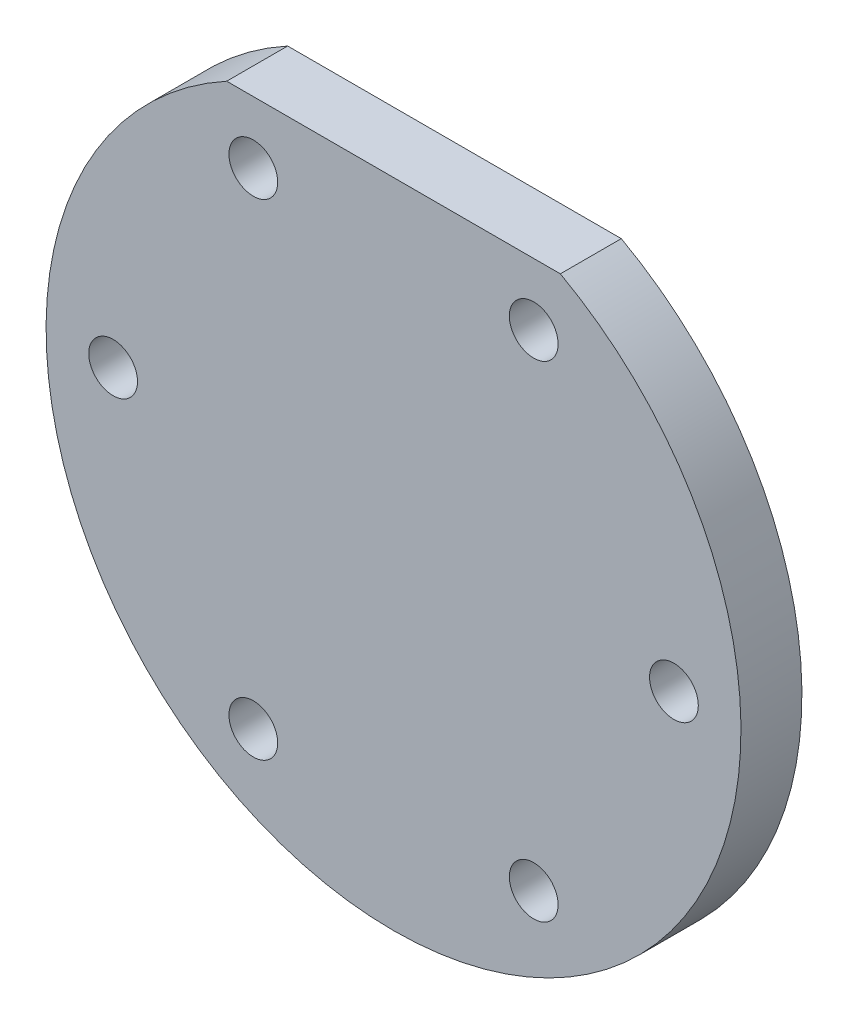
SolidWorks part; units mm, degrees
ref_plane "前视基准面" through (0, 0, 0) normal (0, 0, 1) x (1, 0, 0)
ref_plane "上视基准面" through (0, 0, 0) normal (0, 1, 0) x (1, 0, 0)
ref_plane "右视基准面" through (0, 0, 0) normal (1, 0, 0) x (0, 0, -1)
other "Configuration Table"
sketch "草图1" plane through (0, 0, 0) normal (0, 0, 1) x (1, 0, 0)
  line L0 (-13.6839, 25) -> (13.6839, 25)
  arc A0 (-13.6839, 25) -> (13.6839, 25) centre (0, 0) ccw
  circle A1 centre (0, 0) radius 23 construction
  circle A3 centre (23, 0) radius 2
  circle A4 centre (11.5, -19.9186) radius 2
  circle A5 centre (-11.5, -19.9186) radius 2
  circle A6 centre (-23, 0) radius 2
  circle A7 centre (-11.5, 19.9186) radius 2
  circle A8 centre (11.5, 19.9186) radius 2
  point P18 (0, 0)
  point P19 (0, 0)
  dimension "D1" = 57
  dimension "D2" = 46
  dimension "D4" = 25
  dimension "D3" = 6
extrude "凸台-拉伸1" add sketch "草图1" along normal blind 5
